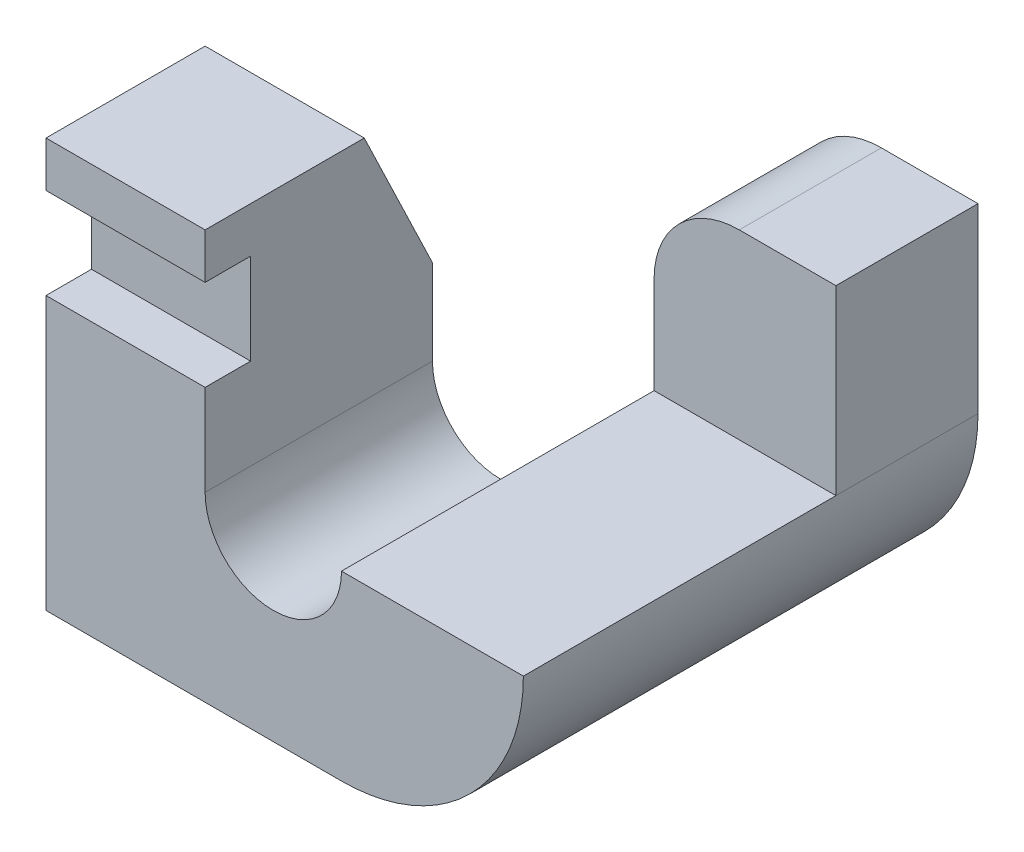
SolidWorks part; units mm, degrees
ref_plane "Front Plane" through (0, 0, 0) normal (0, 0, 1) x (1, 0, 0)
ref_plane "Top Plane" through (0, 0, 0) normal (0, 1, 0) x (1, 0, 0)
ref_plane "Right Plane" through (0, 0, 0) normal (1, 0, 0) x (0, 0, -1)
sketch "Sketch1" plane through (0, 0, 0) normal (0, 0, 1) x (1, 0, 0)
  line L0 (0, 0) -> (52, 0)
  line L2 (0, 0) -> (0, 72)
  line L3 (0, 72) -> (28, 72)
  line L4 (28, 72) -> (28, 32)
  line L5 (52, 32) -> (84, 32)
  arc A0 (28, 32) -> (52, 32) centre (40, 32) ccw
  arc A1 (52, 0) -> (84, 32) centre (52, 32) ccw
  dimension "D6" = 64
  dimension "D2" = 72
  dimension "D3" = 28
  dimension "D4" = 32
  dimension "D5" = 12
extrude "Boss-Extrude1" add sketch "Sketch1" along normal blind 80
sketch "Sketch3" plane through (0, 0, 0) normal (0, 0, -1) x (-1, 0, 0)
  line L0 (-52, 32) -> (-52, 49)
  line L1 (-67, 64) -> (-84, 64)
  line L2 (-84, 64) -> (-84, 32)
  line L3 (-67, 64) -> (-67, 49) construction
  line L5 (0, 0) -> (0, 72)
  line L6 (0, 72) -> (-28, 72)
  line L7 (-28, 72) -> (-28, 32)
  line L8 (-52, 32) -> (-84, 32)
  line L9 (-52, 0) -> (0, 0)
  line L13 (-52, 32) -> (-84, 32)
  arc A0 (-52, 49) -> (-67, 64) centre (-67, 49) ccw
  arc A2 (-52, 32) -> (-28, 32) centre (-40, 32) ccw
  arc A3 (-84, 32) -> (-52, 0) centre (-52, 32) ccw
  point P11 (-67, 64)
  dimension "D4" = 15
  dimension "D1" = 0
extrude "Boss-Extrude2" add sketch "Sketch3" against normal blind 25
sketch "Sketch4" plane through (0, 72, 0) normal (0, 1, 0) x (1, 0, 0)
  line L1 (28, -80) -> (0, -80) construction
  line L3 (28, -80) -> (0, -80)
  line L4 (52, -80) -> (52, -25) construction
  line L5 (52, -40) -> (52, -25)
  line L6 (52, -25) -> (52, 0) construction
  line L7 (52, -25) -> (52, 0)
  line L8 (52, 0) -> (0, 0)
  line L9 (0, 0) -> (0, -40)
  line L10 (52, -40) -> (0, -40)
  point P6 (52, -40)
  line M2 (28, 0) -> (0, 0)
  line M3 (0, 0) -> (0, -80)
  line M5 (28, -80) -> (28, 0)
  dimension "D1" = 40
extrude "Cut-Extrude1" cut sketch "Sketch4" against normal through all contours L10 M5 M2 M3 | L10 L5 L7 L8 M5
sketch "Sketch5" plane through (28, 0, 0) normal (1, 0, 0) x (0, 0, -1)
  line L0 (-80, 72) -> (-80, 64)
  line L1 (-80, 32) -> (-80, 72) construction
  line L2 (-80, 64) -> (-72, 64)
  line L3 (-72, 64) -> (-72, 48)
  line L4 (-72, 48) -> (-80, 48)
  line L5 (-80, 72) -> (-52, 72)
  line L6 (-80, 72) -> (-40, 72) construction
  line L7 (-40, 72) -> (-40, 32) construction
  line L8 (-52, 72) -> (-40, 47)
  line L9 (-40, 47) -> (-40, 72)
  line L10 (-80, 48) -> (-80, 64)
  line L11 (-40, 72) -> (-52, 72)
  line M8 (-40, 32) -> (-40, 72)
  line M9 (-40, 72) -> (-80, 72)
  line M10 (-80, 72) -> (-80, 32)
  dimension "D1" = 8
  dimension "D2" = 16
  dimension "D3" = 8
  dimension "D4" = 28
  dimension "D5" = 25
extrude "Cut-Extrude2" cut sketch "Sketch5" against normal blind 55 contours L8 M9 M8 | L4 L3 L2 M10
